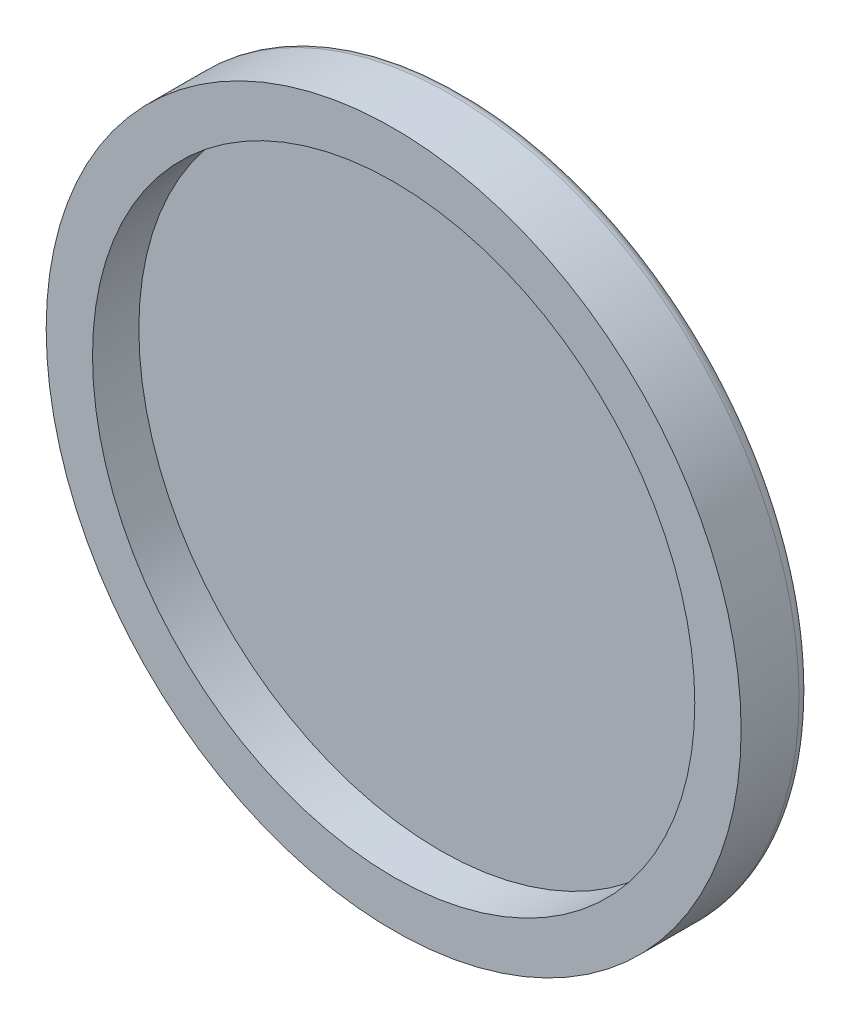
SolidWorks part; units mm, degrees
ref_plane "Front Plane" through (0, 0, 0) normal (0, 0, 1) x (1, 0, 0)
ref_plane "Top Plane" through (0, 0, 0) normal (0, 1, 0) x (1, 0, 0)
ref_plane "Right Plane" through (0, 0, 0) normal (1, 0, 0) x (0, 0, -1)
sketch "Sketch1" plane through (0, 0, 0) normal (0, 0, 1) x (1, 0, 0)
  circle A0 centre (0, 0) radius 13
  circle A1 centre (0, 0) radius 15
  dimension "D1" = 26
  dimension "D2" = 30
extrude "Boss-Extrude1" add sketch "Sketch1" along normal blind 2 contours A0 | A1
sketch "Sketch2" plane through (0, 0, 0) normal (0, 0, -1) x (-1, 0, 0)
  circle A0 centre (0, 0) radius 15
  dimension "D1" = 30
extrude "Boss-Extrude2" add sketch "Sketch2" along normal blind 1
fillet "Fillet1" radius 0.5 1 edges at (-15, 0, -1)
